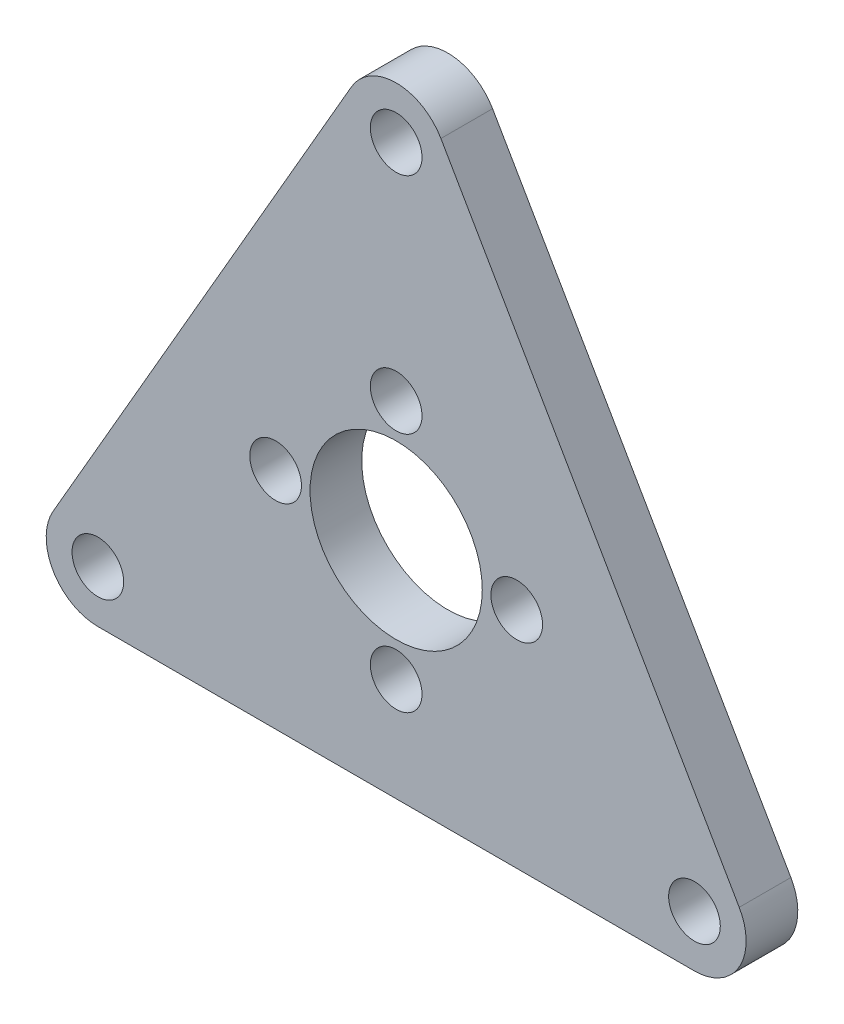
SolidWorks part; units mm, degrees
material "Thornel Mat VMA"
ref_plane "前视基准面" through (0, 0, 0) normal (0, 0, 1) x (1, 0, 0)
ref_plane "上视基准面" through (0, 0, 0) normal (0, 1, 0) x (1, 0, 0)
ref_plane "右视基准面" through (0, 0, 0) normal (1, 0, 0) x (0, 0, -1)
sketch "草图1" plane through (0, 0, 0) normal (0, 0, 1) x (1, 0, 0)
  line L0 (0, 20) -> (-17.3205, -10) construction
  line L1 (-17.3205, -10) -> (17.3205, -10) construction
  line L2 (17.3205, -10) -> (0, 20) construction
  line L3 (-2.5981, 21.5) -> (-19.9186, -8.5)
  line L4 (-17.3205, -13) -> (17.3205, -13)
  line L5 (19.9186, -8.5) -> (2.5981, 21.5)
  circle A0 centre (0, 0) radius 20 construction
  circle A1 centre (-17.3205, -10) radius 1.5
  circle A2 centre (0, 20) radius 1.5
  circle A3 centre (17.3205, -10) radius 1.5
  circle A4 centre (0, 0) radius 5
  circle A5 centre (0, 0) radius 7 construction
  circle A6 centre (0, 7) radius 1.5
  circle A7 centre (0, -7) radius 1.5
  circle A8 centre (0, 0) radius 26 construction
  arc A9 (-19.9186, -8.5) -> (-17.3205, -13) centre (-17.3205, -10) ccw
  arc A10 (17.3205, -13) -> (19.9186, -8.5) centre (17.3205, -10) ccw
  arc A11 (-2.5981, 21.5) -> (2.5981, 21.5) centre (0, 20) cw
  point P23 (-22.5167, -13)
  point P26 (22.5167, -13)
  point P29 (0, 26)
  dimension "D1" = 40
  dimension "D2" = 3
  dimension "D3" = 10
  dimension "D4" = 14
  dimension "D5" = 3
  dimension "D6" = 3
  dimension "D7" = 3
extrude "凸台-拉伸1" add sketch "草图1" along normal blind 3
sketch "草图2" plane through (0, 0, 0) normal (0, 0, 1) x (1, 0, 0)
  line L0 (-19.2815, 0) -> (24.6163, 0) construction
  line L1 (0, 24.2307) -> (0, -16.3646) construction
  circle A0 centre (7, 0) radius 1.5
  circle A1 centre (-7, 0) radius 1.5
  dimension "D1" = 3
  dimension "D2" = 14
extrude "切除-拉伸2" cut sketch "草图2" along normal blind 10
